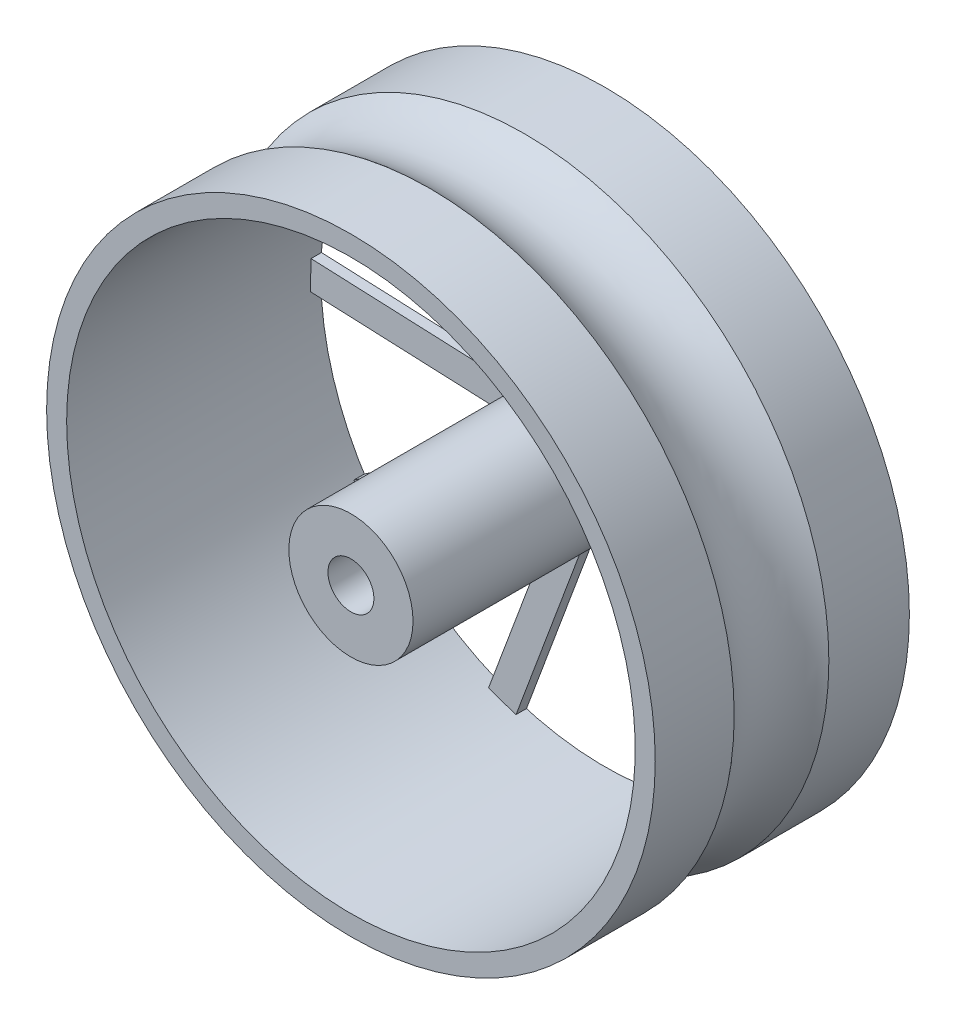
SolidWorks part; units mm, degrees
material "ABS"
ref_plane "Front Plane" through (0, 0, 0) normal (0, 0, 1) x (1, 0, 0)
ref_plane "Top Plane" through (0, 0, 0) normal (0, 1, 0) x (1, 0, 0)
ref_plane "Right Plane" through (0, 0, 0) normal (1, 0, 0) x (0, 0, -1)
sketch "Sketch1" plane through (0, 0, 0) normal (0, 0, 1) x (1, 0, 0)
  circle A0 centre (0, 0) radius 14.8463 construction
  circle A1 centre (0, 0) radius 13.3223
  circle A2 centre (0, 0) radius 2.7178
  circle A3 centre (0, 0) radius 1.0058
  circle A4 centre (0, 0) radius 12.446
  dimension "D1" = 29.6926
  dimension "D3" = 5.4356
  dimension "D4" = 2.0117
  dimension "D5" = 24.892
  dimension "D2" = 1.524
extrude "Boss-Extrude1" add sketch "Sketch1" along normal blind 11.1252 contours A1 | A4 | A2 | A3
sketch "Sketch2" plane through (0, 0, 0) normal (0, 0, -1) x (-1, 0, 0)
  line L0 (-3.4424, 11.9605) -> (0, 2.7178)
  line L1 (0, 2.7178) -> (0, 2.7124)
  line L2 (3.4424, 11.9605) -> (0, 2.7178)
  line L3 (-3.4424, 11.9605) -> (-4.6437, 11.5472)
  line L4 (-4.6437, 11.5472) -> (-1.2431, 2.4168)
  line L5 (-1.2431, 2.4168) -> (0, 2.7124)
  line L6 (0, 12.7489) -> (0, -12.7489) construction
  line L7 (3.4424, 11.9605) -> (4.6437, 11.5472)
  line L8 (4.6437, 11.5472) -> (1.2431, 2.4168)
  line L9 (1.2431, 2.4168) -> (0, 2.7124)
  line L10 (3.4424, 11.9605) -> (4.6437, 11.5472)
  line L11 (1.2431, 2.4168) -> (0, 2.7124)
  line L12 (3.4424, 11.9605) -> (4.6437, 11.5472)
  line L13 (3.4424, 11.9605) -> (0, 2.7178)
  line L14 (0, 2.7124) -> (1.2431, 2.4168)
  line L15 (4.6437, 11.5472) -> (3.4424, 11.9605)
  line L16 (3.4424, 11.9605) -> (0, 2.7178)
  line L17 (0, 2.7178) -> (0, 2.7124)
  line L18 (0, 2.7124) -> (1.2431, 2.4168)
  line L19 (1.5975, 2.1987) -> (1.5943, 2.1943)
  line L20 (0.4149, 2.6859) -> (1.5943, 2.1943)
  line L21 (3.0304, 12.0714) -> (0.4149, 2.6859)
  line L22 (4.2452, 11.6996) -> (3.0304, 12.0714)
  line L23 (4.2452, 11.6996) -> (1.5975, 2.1987)
  line L24 (2.5848, 0.8398) -> (2.5796, 0.8382)
  line L25 (1.9144, 1.9291) -> (2.5796, 0.8382)
  line L26 (9.5471, 7.9847) -> (1.9144, 1.9291)
  line L27 (10.3113, 6.9699) -> (9.5471, 7.9847)
  line L28 (10.3113, 6.9699) -> (2.5848, 0.8398)
  line L29 (2.5848, -0.8398) -> (2.5796, -0.8382)
  line L30 (2.6827, 0.4354) -> (2.5796, -0.8382)
  line L31 (12.4171, 0.8482) -> (2.6827, 0.4354)
  line L32 (12.4388, -0.4221) -> (12.4171, 0.8482)
  line L33 (12.4388, -0.4221) -> (2.5848, -0.8398)
  line L34 (1.5975, -2.1987) -> (1.5943, -2.1943)
  line L35 (2.4263, -1.2246) -> (1.5943, -2.1943)
  line L36 (10.5442, -6.6124) -> (2.4263, -1.2246)
  line L37 (9.8152, -7.6528) -> (10.5442, -6.6124)
  line L38 (9.8152, -7.6528) -> (1.5975, -2.1987)
  line L39 (0, -2.7178) -> (0, -2.7124)
  line L40 (1.2431, -2.4168) -> (0, -2.7124)
  line L41 (4.6437, -11.5472) -> (1.2431, -2.4168)
  line L42 (3.4424, -11.9605) -> (4.6437, -11.5472)
  line L43 (3.4424, -11.9605) -> (0, -2.7178)
  line L44 (-1.5975, -2.1987) -> (-1.5943, -2.1943)
  line L45 (-0.4149, -2.6859) -> (-1.5943, -2.1943)
  line L46 (-3.0304, -12.0714) -> (-0.4149, -2.6859)
  line L47 (-4.2452, -11.6996) -> (-3.0304, -12.0714)
  line L48 (-4.2452, -11.6996) -> (-1.5975, -2.1987)
  line L49 (-2.5848, -0.8398) -> (-2.5796, -0.8382)
  line L50 (-1.9144, -1.9291) -> (-2.5796, -0.8382)
  line L51 (-9.5471, -7.9847) -> (-1.9144, -1.9291)
  line L52 (-10.3113, -6.9699) -> (-9.5471, -7.9847)
  line L53 (-10.3113, -6.9699) -> (-2.5848, -0.8398)
  line L54 (-2.5848, 0.8398) -> (-2.5796, 0.8382)
  line L55 (-2.6827, -0.4354) -> (-2.5796, 0.8382)
  line L56 (-12.4171, -0.8482) -> (-2.6827, -0.4354)
  line L57 (-12.4388, 0.4221) -> (-12.4171, -0.8482)
  line L58 (-12.4388, 0.4221) -> (-2.5848, 0.8398)
  line L59 (-1.5975, 2.1987) -> (-1.5943, 2.1943)
  line L60 (-2.4263, 1.2246) -> (-1.5943, 2.1943)
  line L61 (-10.5442, 6.6124) -> (-2.4263, 1.2246)
  line L62 (-9.8152, 7.6528) -> (-10.5442, 6.6124)
  line L63 (-9.8152, 7.6528) -> (-1.5975, 2.1987)
  circle A0 centre (0, 0) radius 12.446 construction
  circle A1 centre (0, 0) radius 2.7178 construction
  point P8 (0, 2.7178)
  point P63 (0, 0)
  circle M8 centre (0, 0) radius 2.7178
  dimension "D1" = 9.8629
  dimension "D2" = 1.27
  dimension "D3" = 10
extrude "Boss-Extrude2" add sketch "Sketch2" against normal blind 0.4572 contours L3 L4 L0 M8 | L63 L62 L61 M8 | L58 L57 L56 M8 | L53 L52 L51 M8 | L48 L47 L46 M8 | L38 L37 L36 M8 | L33 L32 L31 M8 | L28 L27 L26 M8 | L23 L8 M8 | L23 L15 L22 L16 L21 L8 M8 | L21 L16 M8 | L41 L40 L39 L43 L42
sketch "Sketch5" plane through (0, 0, 0) normal (1, 0, 0) x (0, 0, -1)
  circle A0 centre (-5.5972, 15.7442) radius 3.1873
  dimension "D1" = 6.3746
sketch "Sketch6" plane through (0, 0, 0) normal (1, 0, 0) x (0, 0, -1)
  line L0 (-11.6063, 0) -> (10.7428, 0)
  line L1 (6.1189, 0) -> (-6.1189, 0) construction
revolve "Cut-Revolve1" cut sketch "Sketch5" angle 360 about L0
